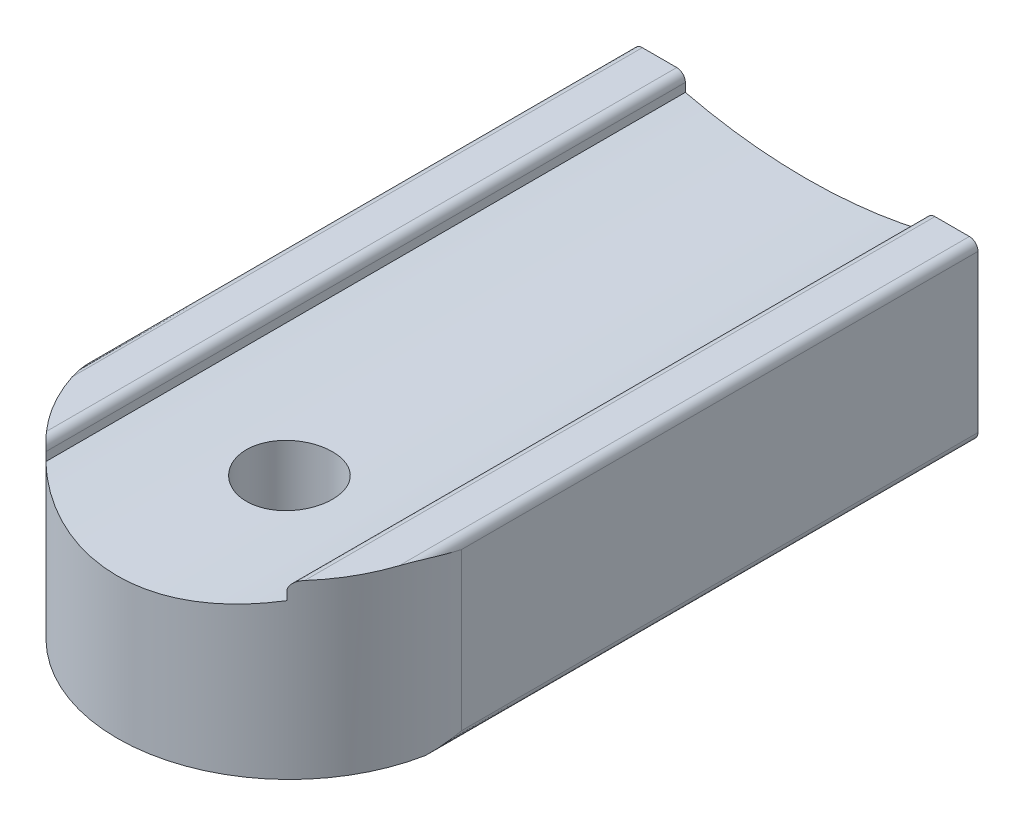
SolidWorks part; units mm, degrees
material "PET"
ref_plane "Alzado" through (0, 0, 0) normal (0, 0, 1) x (1, 0, 0)
ref_plane "Planta" through (0, 0, 0) normal (0, 1, 0) x (1, 0, 0)
ref_plane "Vista lateral" through (0, 0, 0) normal (1, 0, 0) x (0, 0, -1)
sketch "Croquis1" plane through (0, 0, 0) normal (0, 0, 1) x (1, 0, 0)
  line L0 (-13.731, 11.1484) -> (-13.731, 2.0357)
  line L1 (-13.231, 11.6484) -> (-11.231, 11.6484)
  line L2 (-10.731, 11.1484) -> (-10.731, 10.6484)
  line L8 (-13.3561, 1.5516) -> (-12.1695, 1.2449)
  line L9 (-11.7946, 0.7608) -> (-11.7946, 0.4429)
  line L13 (-10.0124, 1.7815) -> (-10.0124, 1.7815)
  line L14 (-11.731, 3.1973) -> (-11.6691, 3.1813)
  line L15 (-11.731, 8.8365) -> (-11.731, 3.1973)
  line L16 (-11.731, 8.8365) -> (-11.731, 8.8365)
  line L17 (-11.731, 8.8365) -> (-11.731, 8.8365)
  line L18 (5.769, 11.6484) -> (3.769, 11.6484)
  line L19 (3.269, 11.1484) -> (3.269, 10.6484)
  line L20 (6.269, 11.1484) -> (6.269, 2.0357)
  line L21 (5.8941, 1.5516) -> (4.7075, 1.2449)
  line L22 (4.3327, 0.7608) -> (4.3327, 0.4429)
  line L23 (4.269, 8.8365) -> (4.269, 3.1973)
  arc A0 (-10.731, 10.6484) -> (-3.731, 9.8203) centre (-3.731, 39.8203) ccw
  arc A1 (-3.731, -1.1797) -> (-11.5837, 0.1565) centre (-2.6698, 28.8016) cw
  arc A2 (-11.7946, 0.7608) -> (-12.1695, 1.2449) centre (-12.2946, 0.7608) ccw
  arc A3 (-11.231, 11.6484) -> (-10.731, 11.1484) centre (-11.231, 11.1484) cw
  arc A4 (-13.731, 11.1484) -> (-13.231, 11.6484) centre (-13.231, 11.1484) cw
  arc A5 (-13.3561, 1.5516) -> (-13.731, 2.0357) centre (-13.231, 2.0357) cw
  arc A6 (-11.5837, 0.1565) -> (-11.7946, 0.4429) centre (-11.4946, 0.4429) cw
  arc A7 (-3.6602, 0.8191) -> (-10.0124, 1.7815) centre (-2.6698, 28.8016) cw
  arc A8 (-10.0124, 1.7815) -> (-10.0124, 1.7815) centre (-10.0124, 1.7815) cw
  arc A9 (-10.0124, 1.7815) -> (-11.6691, 3.1813) centre (-12.2946, 0.7608) ccw
  arc A10 (-11.731, 3.1973) -> (-11.731, 3.1973) centre (-11.731, 3.1973) cw
  arc A11 (-11.731, 8.8365) -> (-11.731, 8.8365) centre (-11.731, 8.8365) cw
  arc A12 (-11.731, 8.8365) -> (-11.731, 8.8365) centre (-11.731, 8.8365) cw
  arc A13 (-11.731, 8.8365) -> (-3.731, 7.8203) centre (-3.731, 39.8203) ccw
  arc A14 (6.269, 11.1484) -> (5.769, 11.6484) centre (5.769, 11.1484) ccw
  arc A15 (3.769, 11.6484) -> (3.269, 11.1484) centre (3.769, 11.1484) ccw
  arc A16 (5.8941, 1.5516) -> (6.269, 2.0357) centre (5.769, 2.0357) ccw
  arc A17 (4.3327, 0.7608) -> (4.7075, 1.2449) centre (4.8327, 0.7608) cw
  arc A18 (4.1218, 0.1565) -> (4.3327, 0.4429) centre (4.0327, 0.4429) ccw
  arc A19 (-3.731, -1.1797) -> (4.1218, 0.1565) centre (-4.7921, 28.8016) ccw
  arc A20 (-3.8017, 0.8191) -> (2.5505, 1.7815) centre (-4.7921, 28.8016) ccw
  arc A21 (2.5505, 1.7815) -> (4.2071, 3.1813) centre (4.8327, 0.7608) cw
  arc A22 (4.269, 8.8365) -> (-3.731, 7.8203) centre (-3.731, 39.8203) cw
  arc A23 (3.269, 10.6484) -> (-3.731, 9.8203) centre (-3.731, 39.8203) cw
  point P14 (-11.7946, 1.148)
  point P20 (-10.731, 11.6484)
  point P23 (-13.731, 11.6484)
  point P26 (-13.731, 1.6484)
  dimension "D4" = 30
  dimension "D6" = 1
  dimension "D8" = 30
  dimension "D5" = 0.5
  dimension "D7" = 0.5
  dimension "D10" = 0.5
  dimension "D11" = 0.5
  dimension "D12" = 0.3
  dimension "D1" = 10
  dimension "D2" = 3
  dimension "D3" = 11
  dimension "D9" = 2
  dimension "D13" = 2
extrude "Saliente-Extruir1" add sketch "Croquis1" along normal blind 40
sketch "Croquis2" plane through (0, 0, 0) normal (0, 1, 0) x (1, 0, 0)
  line L0 (-13.731, -40) -> (-13.731, 0) construction
  line L1 (6.269, -40) -> (6.269, 0) construction
  line L2 (-13.731, -30) -> (-13.731, -43.2894)
  line L3 (-13.731, -43.2894) -> (6.269, -43.2894)
  line L4 (6.269, -43.2894) -> (6.269, -30)
  arc A0 (-13.731, -30) -> (6.269, -30) centre (-3.731, -30) ccw
  circle A1 centre (-3.731, -30) radius 2.5
  dimension "D1" = 10
  dimension "D2" = 5
extrude "Cortar-Extruir1" cut sketch "Croquis2" along normal mid plane 45
ref_plane "Plano1" through (0, 1.6484, 0) normal (0, 1, 0) x (1, 0, 0)
sketch "Croquis5" plane through (0, 1.6484, 0) normal (0, 1, 0) x (1, 0, 0)
  line L0 (-13.731, 0) -> (-13.731, -40.7774)
  line L1 (-13.731, -40.7774) -> (6.269, -40.7774)
  line L2 (6.269, -40.7774) -> (6.269, 0)
  arc A0 (-13.731, 0) -> (6.269, 0) centre (-3.731, 0) ccw
extrude "Cortar-Extruir5" cut sketch "Croquis5" against normal blind 14
sketch "Croquis6" plane through (0, 1.6484, 0) normal (0, -1, 0) x (1, 0, 0)
  circle A0 centre (-3.731, 30) radius 4
  circle A1 centre (-3.731, 30) radius 2.5
  dimension "D1" = 8
extrude "Saliente-Extruir2" add sketch "Croquis6" along normal blind 1 contours A0 | A1
